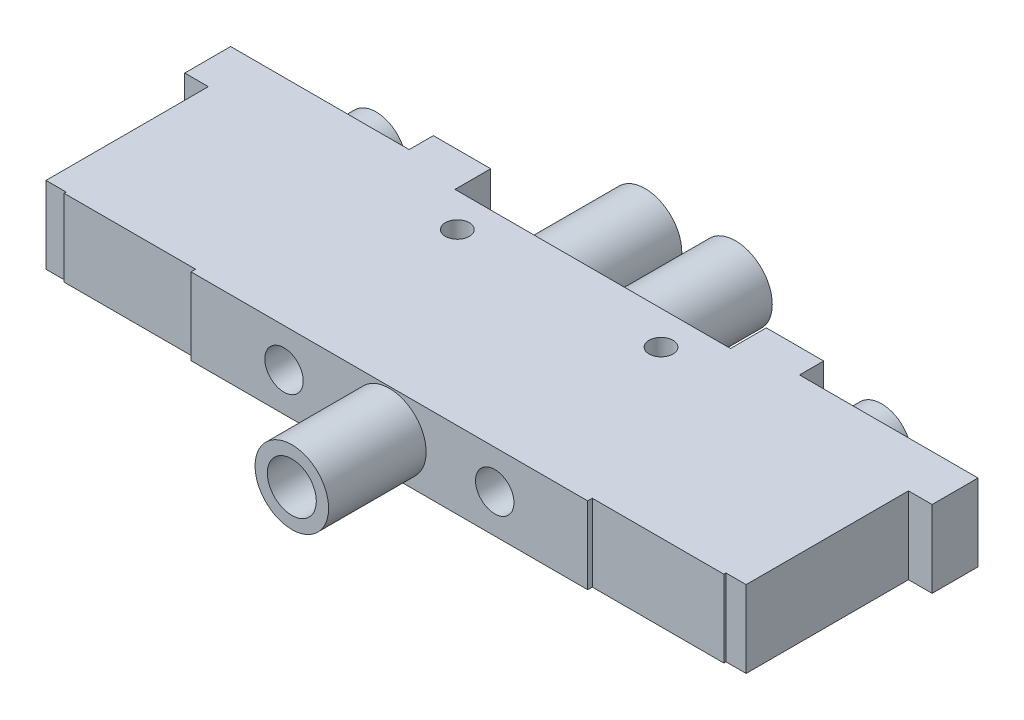
SolidWorks part; units mm, degrees
ref_plane "Front Plane" through (0, 0, 0) normal (0, 0, 1) x (1, 0, 0)
ref_plane "Top Plane" through (0, 0, 0) normal (0, 1, 0) x (1, 0, 0)
ref_plane "Right Plane" through (0, 0, 0) normal (1, 0, 0) x (0, 0, -1)
sketch "Sketch1" plane through (0, 0, 0) normal (0, 1, 0) x (1, 0, 0)
  line L0 (-18.3007, 0) -> (18.3007, 0)
  line L1 (18.3007, 0) -> (18.3007, 4.7498)
  line L2 (18.3007, 4.7498) -> (25.9207, 4.7498)
  line L3 (25.9207, 4.7498) -> (25.9207, 1.5367)
  line L4 (25.9207, 1.5367) -> (49.6316, 1.5367)
  line L5 (0, 0) -> (0, -27.0129) construction
  line L6 (-26.3398, -26.4033) -> (-26.3398, -27.0129)
  line L7 (49.6316, 1.5367) -> (49.6316, -4.5593)
  line L8 (49.6316, -4.5593) -> (46.4947, -4.5593)
  line L9 (46.4947, -4.5593) -> (46.4947, -26.1239)
  line L10 (46.4947, -26.1239) -> (43.815, -26.1239)
  line L11 (43.815, -26.1239) -> (43.815, -26.4033)
  line L12 (43.815, -26.4033) -> (26.3398, -26.4033)
  line L13 (26.3398, -26.4033) -> (26.3398, -27.0129)
  line L14 (26.3398, -27.0129) -> (-26.3398, -27.0129)
  line L15 (-43.815, -26.4033) -> (-26.3398, -26.4033)
  line L16 (-43.815, -26.1239) -> (-43.815, -26.4033)
  line L17 (-46.4947, -26.1239) -> (-43.815, -26.1239)
  line L18 (-46.4947, -4.5593) -> (-46.4947, -26.1239)
  line L19 (-49.6316, -4.5593) -> (-46.4947, -4.5593)
  line L20 (-49.6316, 1.5367) -> (-49.6316, -4.5593)
  line L21 (-25.9207, 1.5367) -> (-49.6316, 1.5367)
  line L22 (-25.9207, 4.7498) -> (-25.9207, 1.5367)
  line L23 (-18.3007, 4.7498) -> (-25.9207, 4.7498)
  line L24 (-18.3007, 0) -> (-18.3007, 4.7498)
  circle A0 centre (13.5255, -4.4577) radius 1.5875
  circle A1 centre (-13.5255, -4.4577) radius 1.5875
  dimension "D13" = 2.8702
  dimension "D14" = 3.175
  dimension "D1" = 27.0129
  dimension "D2" = 18.3007
  dimension "D3" = 7.62
  dimension "D4" = 4.7498
  dimension "D5" = 3.2131
  dimension "D6" = 23.7109
  dimension "D7" = 6.096
  dimension "D8" = 3.1369
  dimension "D9" = 21.5646
  dimension "D10" = 27.94
  dimension "D11" = 2.6797
  dimension "D12" = 20.1549
  dimension "D15" = 11.938
extrude "Boss-Extrude1" add sketch "Sketch1" along normal blind 10.2235
sketch "Sketch2" plane through (0, 0, 27.0129) normal (0, 0, 1) x (1, 0, 0)
  line L0 (0, 10.2235) -> (0, 5.1118) construction
  line L1 (-26.3398, 10.2235) -> (26.3398, 10.2235) construction
  line L2 (0, 5.1118) -> (-26.3398, 5.1117) construction
  line L3 (-26.3398, 10.2235) -> (-26.3398, 0) construction
  circle A0 centre (0, 5.1118) radius 4.8832
  circle A1 centre (0, 5.1118) radius 3.2512
  dimension "D1" = 9.7663
  dimension "D2" = 6.5024
extrude "Boss-Extrude2" add sketch "Sketch2" along normal blind 12.954
sketch "Sketch3" plane through (0, 0, 0) normal (0, 0, -1) x (-1, 0, 0)
  line L0 (0, 0) -> (0, 10.2235) construction
  line L1 (-18.3007, 10.2235) -> (18.3007, 10.2235) construction
  line L2 (6.0071, 5.1118) -> (0, 5.1117) construction
  line L3 (0, 5.1117) -> (-6.0071, 5.1117) construction
  circle A0 centre (6.0071, 5.1118) radius 4.8832
  circle A1 centre (-6.0071, 5.1117) radius 4.8832
  circle A2 centre (0, 5.1118) radius 4.8832 construction
  circle A3 centre (-6.0071, 5.1117) radius 3.2512
  circle A4 centre (6.0071, 5.1118) radius 3.2512
  circle A5 centre (0, 5.1118) radius 3.2512 construction
  dimension "D1" = 21.7805
extrude "Boss-Extrude3" add sketch "Sketch3" along normal blind 12.954
hole_wizard "Tap Drill for 1/4-20 Tap1" positions "Sketch5" profile "Sketch4" hole size "1/4-20" standard "Ansi Inch"
sketch "Sketch5" plane through (0, 0, 27.0129) normal (0, 0, 1) x (1, 0, 0)
  line L0 (-13.9954, 5.1118) -> (13.9954, 5.1118) construction
  line L2 (0, 5.1118) -> (0, 0) construction
  line L3 (-26.3398, 0) -> (26.3398, 0) construction
  line L5 (0, 5.1118) -> (0, 10.2235) construction
  line L6 (-26.3398, 10.2235) -> (26.3398, 10.2235) construction
  point P0 (-13.9954, 5.1118)
  point P1 (13.9954, 5.1118)
  dimension "D1" = 27.9908
sketch "Sketch4" plane through (-13.9954, 5.1118, 27.0129) normal (1, 0, 0) x (0, -1, 0)
  line L0 (0, 0) -> (0, 10.5889)
  line L1 (0, 10.5889) -> (2.5527, 9.0551)
  line L2 (2.5527, 9.0551) -> (2.5527, 0)
  line L5 (2.5527, 0) -> (0, 0)
  line L10 (0, 10.5889) -> (-2.5527, 9.0551) construction
  line L11 (0, -6.35) -> (0, 107.95) construction
  dimension "Hole Dia." = 5.1054
  dimension "Hole Depth" = 9.0551
  dimension "Drill Angle" = 118
sketch "Sketch6" plane through (0, 0, -1.5367) normal (0, 0, -1) x (-1, 0, 0)
  line L0 (-25.9207, 10.2235) -> (-25.9207, 0) construction
  line L2 (0, 10.3171) -> (0, 0) construction
  circle A0 centre (-33.5661, 5.1117) radius 4.0005
  circle A1 centre (33.5661, 5.1117) radius 4.0005
  point P4 (-25.9207, 5.1117)
  dimension "D1" = 8.001
  dimension "D2" = 3.6449
extrude "Boss-Extrude4" add sketch "Sketch6" along normal blind 3.2512
